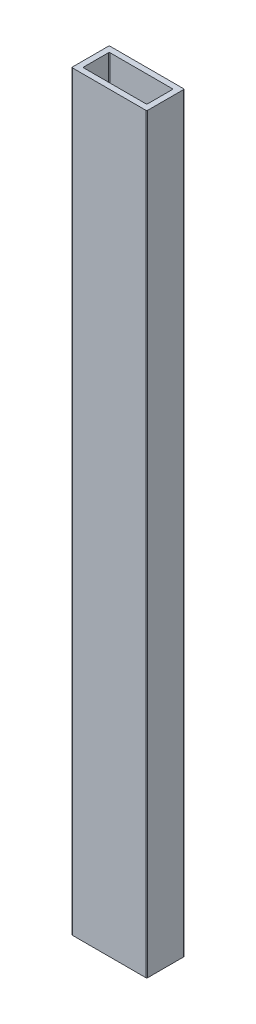
SolidWorks part; units mm, degrees
ref_plane "Спереди" through (0, 0, 0) normal (0, 0, 1) x (1, 0, 0)
ref_plane "Сверху" through (0, 0, 0) normal (0, 1, 0) x (1, 0, 0)
ref_plane "Справа" through (0, 0, 0) normal (1, 0, 0) x (0, 0, -1)
sketch "Эскиз1" plane through (0, 0, 0) normal (0, 1, 0) x (1, 0, 0)
  line L0 (8.5, 3.5) -> (-8.5, 3.5)
  line L1 (10, 5) -> (-10, 5)
  line L2 (10, 5) -> (10, -5)
  line L3 (10, -5) -> (-10, -5)
  line L4 (-10, 5) -> (-10, -5)
  line L5 (10, 5) -> (-10, -5) construction
  line L6 (10, -5) -> (-10, 5) construction
  line L7 (-8.5, 3.5) -> (-8.5, -3.5)
  line L8 (8.5, -3.5) -> (-8.5, -3.5)
  line L9 (8.5, 3.5) -> (8.5, -3.5)
  point P0 (0, 0)
  dimension "D1" = 20
  dimension "D2" = 10
  dimension "D3" = 1.5
extrude "Бобышка-Вытянуть1" add sketch "Эскиз1" along normal blind 200
fillet "Скругление1" radius 0.2 8 edges at (-10, 100, 5) (10, 100, -5) (8.5, 100, -3.5) (8.5, 100, 3.5) (-8.5, 100, 3.5) (-8.5, 100, -3.5) (-10, 100, -5) (10, 100, 5)
